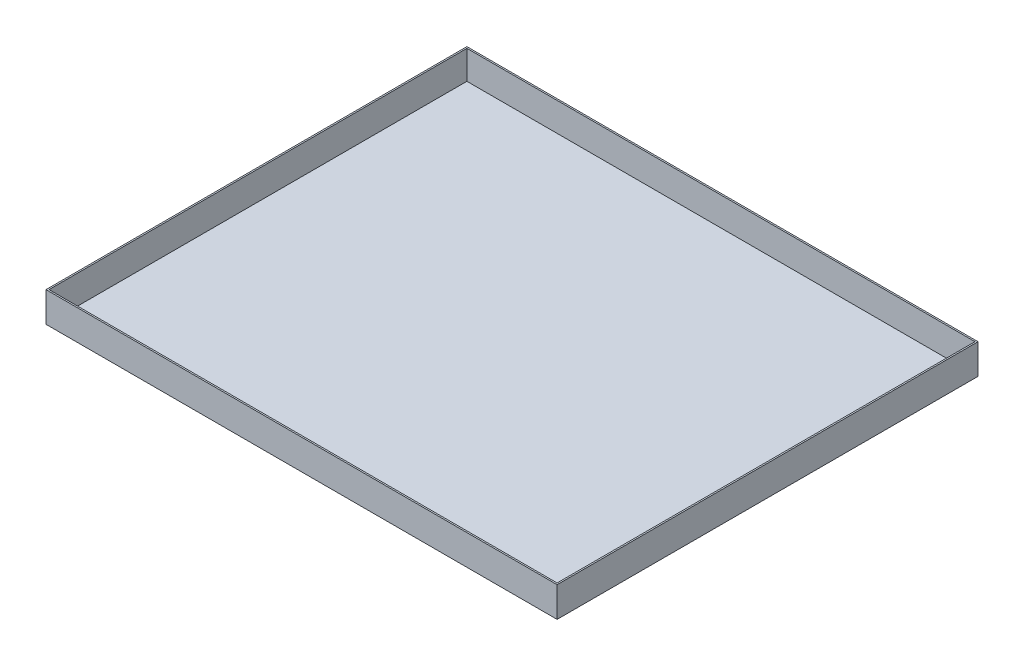
SolidWorks part; units mm, degrees
material "1060 Alloy"
ref_plane "Front Plane" through (0, 0, 0) normal (0, 0, 1) x (1, 0, 0)
ref_plane "Top Plane" through (0, 0, 0) normal (0, 1, 0) x (1, 0, 0)
ref_plane "Right Plane" through (0, 0, 0) normal (1, 0, 0) x (0, 0, -1)
sketch "Sketch1" plane through (0, 0, 0) normal (0, 1, 0) x (1, 0, 0)
  line L1 (-85, 70) -> (85, 70)
  line L2 (-85, 70) -> (-85, -70)
  line L3 (-85, -70) -> (85, -70)
  line L4 (85, 70) -> (85, -70)
  line L5 (-85, 70) -> (85, -70) construction
  line L6 (-85, -70) -> (85, 70) construction
  point P0 (0, 0)
  dimension "D1" = 170
  dimension "D2" = 140
extrude "Boss-Extrude1" add sketch "Sketch1" along normal blind 10 contours L2 L3 L4 L1
shell "Shell1" thickness 0.5
